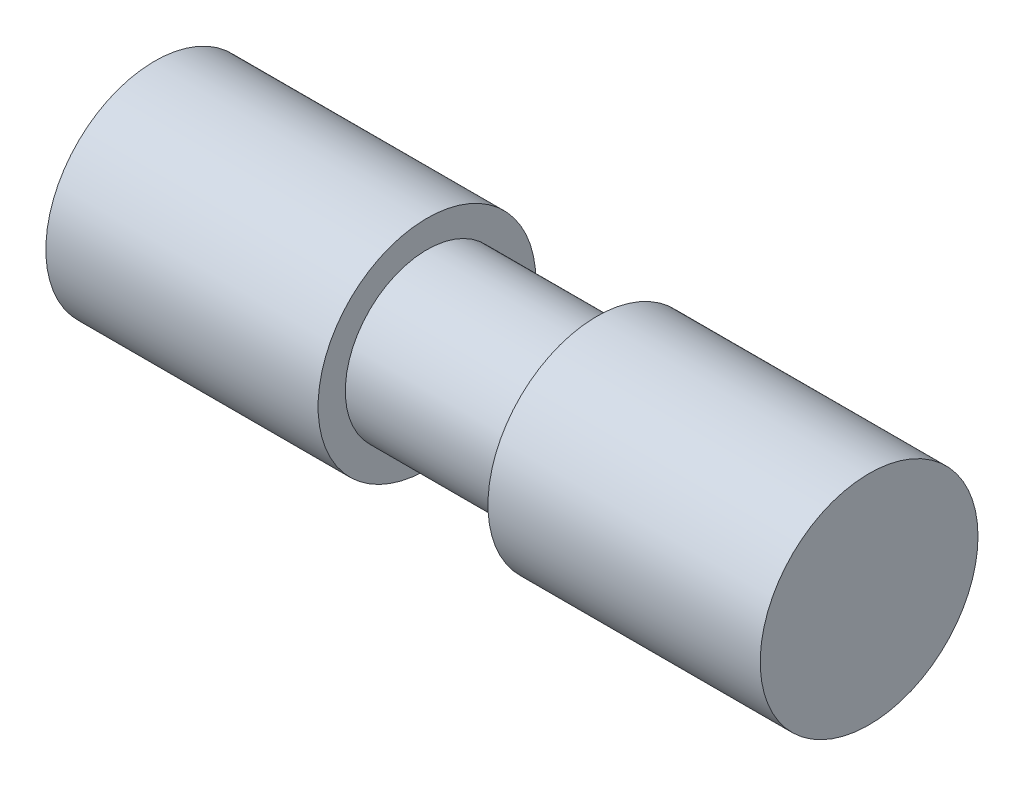
SolidWorks part; units mm, degrees
ref_plane "前视基准面" through (0, 0, 0) normal (0, 0, 1) x (1, 0, 0)
ref_plane "上视基准面" through (0, 0, 0) normal (0, 1, 0) x (1, 0, 0)
ref_plane "右视基准面" through (0, 0, 0) normal (1, 0, 0) x (0, 0, -1)
ref_plane "基准面1" through (-162.4, 0, 0) normal (1, 0, 0) x (0, 0, -1)
sketch "草图1" plane through (0, 0, 0) normal (1, 0, 0) x (0, 0, -1)
  circle A0 centre (0, 0) radius 40
extrude "凸台-拉伸1" add sketch "草图1" along normal mid plane 100
ref_point "点1"
sketch "草图2" plane through (-162.4, 0, 0) normal (1, 0, 0) x (0, 0, -1)
  circle A0 centre (0, 0) radius 40
extrude "凸台-拉伸2" add sketch "草图2" along normal mid plane 100 separate body
ref_plane "基准面2" through (-112.4, 0, 0) normal (1, 0, 0) x (0, 0, -1)
ref_point "点2"
sketch "草图3" plane through (-112.4, 0, 0) normal (1, 0, 0) x (0, 0, -1)
  circle A0 centre (0, 0) radius 30
extrude "凸台-拉伸3" add sketch "草图3" along normal up to surface (62.4 mm away) contours A0 up to face at (-50, 0, -40)
ref_plane "前视基准面——test" through (0, 0, 0) normal (0, 0, 1) x (1, 0, 0)
